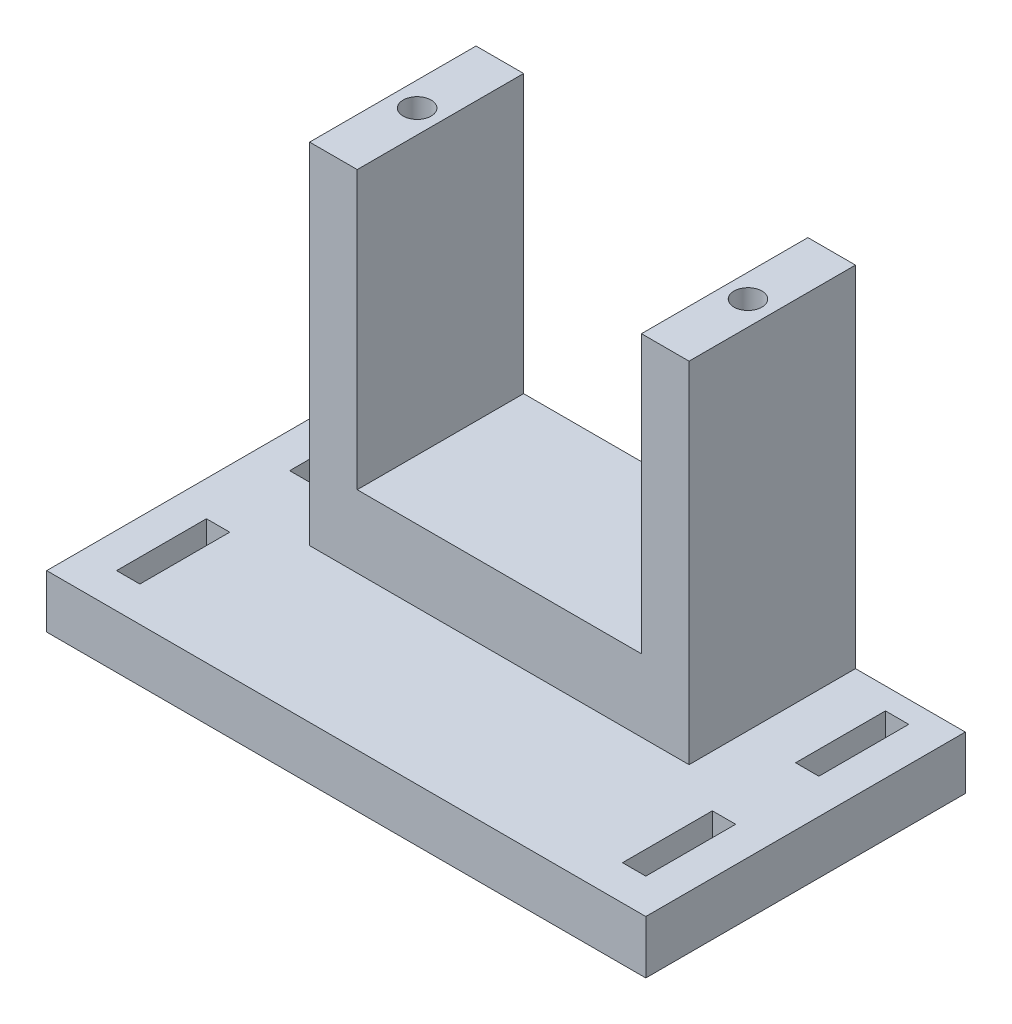
SolidWorks part; units mm, degrees
ref_plane "Front Plane" through (0, 0, 0) normal (0, 0, 1) x (1, 0, 0)
ref_plane "Top Plane" through (0, 0, 0) normal (0, 1, 0) x (1, 0, 0)
ref_plane "Right Plane" through (0, 0, 0) normal (1, 0, 0) x (0, 0, -1)
sketch "Sketch1" plane through (0, 0, 0) normal (0, 0, 1) x (1, 0, 0)
  line L1 (-28.5, 0) -> (28.5, 0)
  line L2 (-28.5, 0) -> (-28.5, 60.5)
  line L3 (-28.5, 60.5) -> (28.5, 60.5)
  line L4 (28.5, 0) -> (28.5, 60.5)
  dimension "D1" = 57
  dimension "D2" = 60.5
extrude "Boss-Extrude1" add sketch "Sketch1" along normal blind 25
sketch "Sketch2" plane through (0, 0, 25) normal (0, 0, 1) x (1, 0, 0)
  line L0 (-28.5, 60.5) -> (-28.5, 0) construction
  line L1 (-21.35, 18.85) -> (21.35, 18.85)
  line L2 (-21.35, 18.85) -> (-21.35, 62.6432)
  line L3 (-21.35, 62.6432) -> (21.35, 62.6432)
  line L4 (21.35, 18.85) -> (21.35, 62.6432)
  line L5 (-28.5, 0) -> (28.5, 0) construction
  dimension "D1" = 42.7
  dimension "D2" = 7.15
  dimension "D3" = 18.85
extrude "Cut-Extrude1" cut sketch "Sketch2" against normal through all
sketch "Sketch3" plane through (0, 0, 0) normal (0, 1, 0) x (1, 0, 0)
  line L1 (-45, 0) -> (45, 0)
  line L2 (-45, 0) -> (-45, -48)
  line L3 (-45, -48) -> (45, -48)
  line L4 (45, 0) -> (45, -48)
  dimension "D1" = 90
  dimension "D2" = 48
extrude "Boss-Extrude2" add sketch "Sketch3" along normal blind 8
sketch "Sketch4" plane through (0, 8, 0) normal (0, 1, 0) x (1, 0, 0)
  line L0 (-45, 0) -> (-45, -48) construction
  line L1 (-39.75, -3.25) -> (-36.25, -3.25)
  line L2 (-39.75, -3.25) -> (-39.75, -16.75)
  line L3 (-39.75, -16.75) -> (-36.25, -16.75)
  line L4 (-36.25, -3.25) -> (-36.25, -16.75)
  line L5 (-45, 0) -> (45, 0) construction
  dimension "D1" = 3.5
  dimension "D2" = 13.5
  dimension "D3" = 5.25
  dimension "D4" = 3.25
extrude "Cut-Extrude2" cut sketch "Sketch4" against normal through all
pattern_linear "LPattern1" count 2 spacing 76 along (1, 0, 0) count 2 spacing 26 along (0, 0, 1) of "Cut-Extrude2"
sketch "Sketch5" plane through (0, 60.5, 0) normal (0, 1, 0) x (1, 0, 0)
  line L0 (-28.5, -25) -> (-28.5, 0) construction
  line L1 (-28.5, 0) -> (-45, 0) construction
  line L2 (28.5, -25) -> (28.5, 0) construction
  line L3 (45, 0) -> (28.5, 0) construction
  circle A0 centre (-24.85, -12.5) radius 2.1
  circle A1 centre (24.85, -12.5) radius 2.1
  dimension "D1" = 4.2
  dimension "D2" = 4.2
  dimension "D3" = 3.65
  dimension "D4" = 12.5
  dimension "D5" = 3.65
  dimension "D6" = 12.5
extrude "Cut-Extrude3" cut sketch "Sketch5" against normal blind 8
